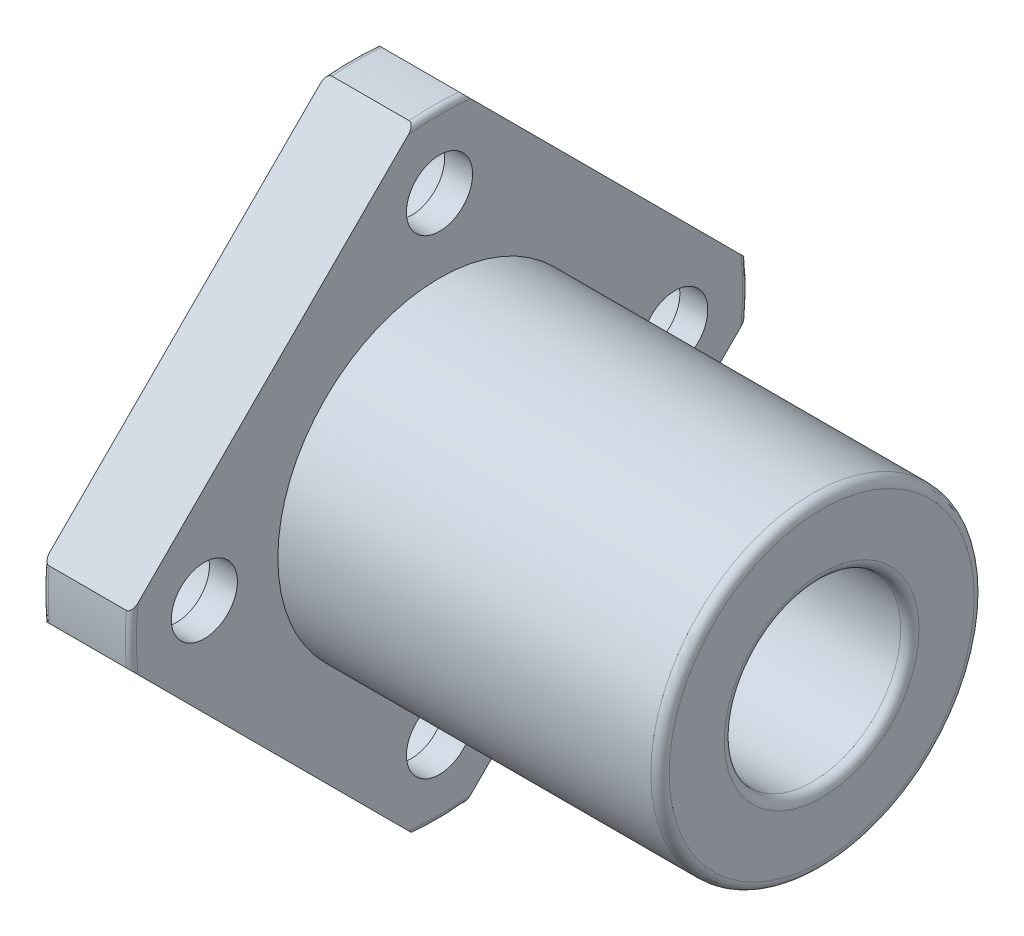
SolidWorks part; units mm, degrees
ref_plane "Plan de face" through (0, 0, 0) normal (0, 0, 1) x (1, 0, 0)
ref_plane "Plan de dessus" through (0, 0, 0) normal (0, 1, 0) x (1, 0, 0)
ref_plane "Plan de droite" through (0, 0, 0) normal (1, 0, 0) x (0, 0, -1)
ref_plane "Plane1" through (0, 0, 0) normal (-1, 0, 0) x (0, -1, 0)
sketch "Sketch1" plane through (0, 0, 0) normal (-1, 0, 0) x (0, -1, 0)
  line L0 (-1.696, 20.9314) -> (-20.9314, 1.696)
  line L1 (-20.9314, -1.696) -> (-1.696, -20.9314)
  line L2 (1.696, -20.9314) -> (20.9314, -1.696)
  line L3 (20.9314, 1.696) -> (1.696, 20.9314)
  arc A0 (-20.9314, 1.696) -> (-20.9314, -1.696) centre (0, 0) ccw
  arc A1 (-1.696, -20.9314) -> (1.696, -20.9314) centre (0, 0) ccw
  arc A2 (20.9314, -1.696) -> (20.9314, 1.696) centre (0, 0) ccw
  arc A3 (1.696, 20.9314) -> (-1.696, 20.9314) centre (0, 0) ccw
extrude "Boss-Extrude1" add sketch "Sketch1" against normal blind 6
sketch "Sketch2" plane through (0, 0, 0) normal (0, 0, 1) x (1, 0, 0)
  line L0 (6, 11) -> (6, 0)
  line L1 (6, 0) -> (32, 0)
  line L2 (32, 0) -> (32, 11)
  line L3 (32, 11) -> (6, 11)
  line L4 (6, 0) -> (32, 0) construction
revolve "Revolve1" add sketch "Sketch2" angle 360 about L4
hole_wizard "CBORE for M4 Hex Head Machine Screw1" positions "Sketch4" profile "Sketch3" counterbore size "M4" standard "ANSI Metric"
sketch "Sketch4" plane through (0, 0, 0) normal (-1, 0, 0) x (0, 0, 1)
  point P0 (0, 16)
  point P1 (0, -16)
  point P2 (-16, 0)
  point P3 (16, 0)
sketch "Sketch3" plane through (0, 16, 0) normal (0, 1, 0) x (0, 0, 1)
  line L0 (0, 0) -> (0, 32)
  line L1 (0, 32) -> (2.25, 32)
  line L3 (2.25, 32) -> (2.25, 4.1)
  line L4 (2.25, 4.1) -> (3.75, 4.1)
  line L5 (3.75, 4.1) -> (3.75, 0)
  line L7 (3.75, 0) -> (0, 0)
  line L11 (0, -6.35) -> (0, 107.95) construction
  dimension "Thru Hole Dia." = 4.5
  dimension "Thru Hole Depth" = 32
  dimension "C'Bore Dia." = 7.5
  dimension "C'Bore Depth" = 4.1
hole_wizard "Ø12.0 (12) Diameter Hole1" positions "Sketch6" profile "Sketch5" hole size "Ø12.0" standard "ANSI Metric"
sketch "Sketch6" plane through (0, 0, 0) normal (-1, 0, 0) x (0, 0, 1)
  point P0 (0, 0)
sketch "Sketch5" plane through (0, 0, 0) normal (0, 1, 0) x (0, 0, 1)
  line L0 (0, 0) -> (0, 32)
  line L1 (0, 32) -> (6, 32)
  line L2 (6, 32) -> (6, 0)
  line L5 (6, 0) -> (0, 0)
  line L11 (0, -6.35) -> (0, 107.95) construction
  dimension "Thru Hole Dia." = 12
  dimension "Thru Hole Depth" = 32
fillet "Fillet1" radius 0.375 8 edges at (0, 0, -21) (6, 21, 0) (6, 0, -21) (0, 0, 21) (6, 0, 21) (0, 21, 0) (0, -21, 0) (6, -21, 0)
fillet "Fillet2" radius 0.625 3 edges at (32, 0, 6) (0, 0, 6) (32, 0, -11)
